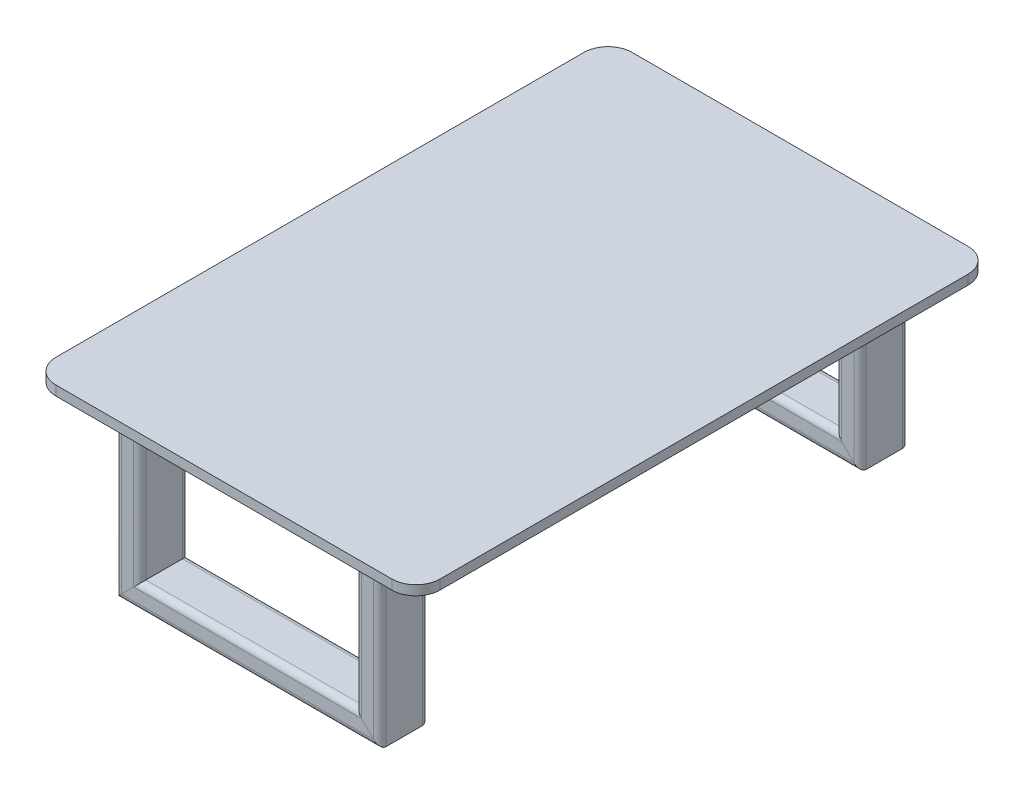
SolidWorks part; units mm, degrees
ref_plane "Alzado" through (0, 0, 0) normal (0, 0, 1) x (1, 0, 0)
ref_plane "Planta" through (0, 0, 0) normal (0, 1, 0) x (1, 0, 0)
ref_plane "Vista lateral" through (0, 0, 0) normal (1, 0, 0) x (0, 0, -1)
sketch3d "Croquis3D2"
  line L1 (-250, -150, 0) -> (250, -150, 0)
  line L2 (-250, -150, 0) -> (-250, 150, 0)
  line L3 (-250, 150, 0) -> (250, 150, 0)
  line L4 (250, -150, 0) -> (250, 150, 0)
  line L5 (-250, -150, 0) -> (250, 150, 0) construction
  line L6 (-250, 150, 0) -> (250, -150, 0) construction
  point P0 (0, 0, 0)
  dimension "D1" = 300
  dimension "D2" = 500
ref_plane "Plano1" through (0, 0, -1000) normal (0, 0, 1) x (1, 0, 0)
sketch "Croquis1" plane through (0, 0, -1000) normal (0, 0, 1) x (1, 0, 0)
  line L0 (-250, 150) -> (250, -150) construction
  line L1 (-250, -150) -> (250, 150) construction
  line L2 (-250, -150) -> (250, -150) construction
  line L3 (250, -150) -> (250, 150) construction
  line L4 (-250, -150) -> (-250, 150) construction
  line L5 (-250, 150) -> (250, 150) construction
  line L6 (-250, 150) -> (250, -150)
  line L7 (-250, -150) -> (250, 150)
  line L8 (-250, -150) -> (250, -150)
  line L9 (250, -150) -> (250, 150)
  line L10 (-250, -150) -> (-250, 150)
  line L11 (-250, 150) -> (250, 150)
other "Tubo rectangular 4 X 2 X 0.25(1)"
ref_plane "Plano2" through (-250, 150, 0) normal (-1, 0, 0) x (0, 1, 0)
sketch "Sketch12" plane through (-250, 150, 0) normal (-1, 0, 0) x (0, 1, 0)
  line L0 (-12.7, -44.45) -> (12.7, -44.45)
  line L1 (-19.05, -38.1) -> (-19.05, 38.1)
  line L2 (12.7, 44.45) -> (-12.7, 44.45)
  line L3 (19.05, 38.1) -> (19.05, -38.1)
  line L4 (-12.7, -50.8) -> (12.7, -50.8)
  line L5 (-25.4, -38.1) -> (-25.4, 38.1)
  line L6 (12.7, 50.8) -> (-12.7, 50.8)
  line L7 (25.4, 38.1) -> (25.4, -38.1)
  line L8 (0, 0) -> (25.4, 0) construction
  line L9 (0, 0) -> (0, 50.8) construction
  arc A0 (25.4, 38.1) -> (12.7, 50.8) centre (12.7, 38.1) ccw
  arc A1 (12.7, -50.8) -> (25.4, -38.1) centre (12.7, -38.1) ccw
  arc A2 (-25.4, -38.1) -> (-12.7, -50.8) centre (-12.7, -38.1) ccw
  arc A3 (-12.7, 50.8) -> (-25.4, 38.1) centre (-12.7, 38.1) ccw
  arc A4 (-12.7, 44.45) -> (-19.05, 38.1) centre (-12.7, 38.1) ccw
  arc A5 (19.05, 38.1) -> (12.7, 44.45) centre (12.7, 38.1) ccw
  arc A6 (12.7, -44.45) -> (19.05, -38.1) centre (12.7, -38.1) ccw
  arc A7 (-19.05, -38.1) -> (-12.7, -44.45) centre (-12.7, -38.1) ccw
  point P3 (0, -50.8)
  point P4 (-25.4, 0)
  point P5 (0, 0)
  point P6 (25.4, -50.8)
  point P7 (-25.4, -50.8)
  point P8 (-25.4, 50.8)
  point P33 (0, 0)
  point P35 (25.4, 50.8)
  point P36 (25.4, 0)
  point P37 (0, 50.8)
  point P38 (0, 0)
  dimension "D1" = 12.7
  dimension "Thickness" = 6.35
  dimension "V_leg" = 101.6
  dimension "H_leg" = 50.8
sketch "Croquis5" plane through (0, 175.4, 0) normal (0, 1, 0) x (1, 0, 0)
  line L1 (-350, -100) -> (350, -100)
  line L2 (-400, -50) -> (-400, 1050)
  line L3 (-350, 1100) -> (350, 1100)
  line L4 (400, -50) -> (400, 1050)
  line L5 (-400, -100) -> (400, 1100) construction
  line L6 (-400, 1100) -> (400, -100) construction
  arc A0 (-350, -100) -> (-400, -50) centre (-350, -50) cw
  arc A1 (350, -100) -> (400, -50) centre (350, -50) ccw
  arc A2 (350, 1100) -> (400, 1050) centre (350, 1050) cw
  arc A3 (-400, 1050) -> (-350, 1100) centre (-350, 1050) cw
  point P0 (0, 500)
  point P5 (0, 0)
  dimension "D4" = 50
  dimension "D1" = 800
  dimension "D2" = 1200
  dimension "D3" = 500
extrude "Saliente-Extruir1" add sketch "Croquis5" along normal blind 20 separate body
